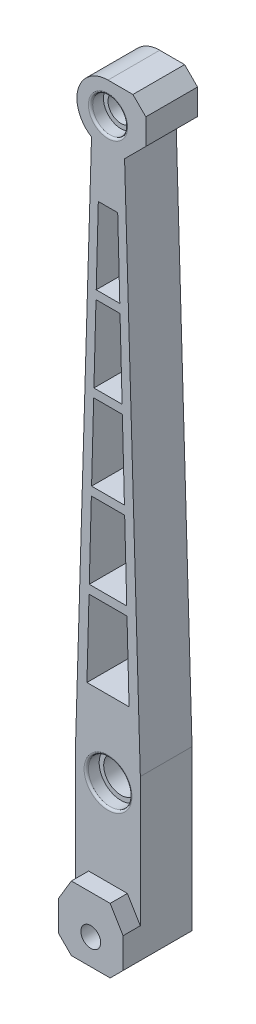
SolidWorks part; units mm, degrees
ref_plane "前视基准面" through (0, 0, 0) normal (0, 0, 1) x (1, 0, 0)
ref_plane "上视基准面" through (0, 0, 0) normal (0, 1, 0) x (1, 0, 0)
ref_plane "右视基准面" through (0, 0, 0) normal (1, 0, 0) x (0, 0, -1)
other "Configuration Table"
sketch "草图1" plane through (0, 0, 0) normal (0, 0, 1) x (1, 0, 0)
  line L0 (0, 15.6534) -> (0, -12.983) construction
  line L1 (-3.6154, 90) -> (-7.5, -40)
  line L2 (-7.5, -80) -> (7.5, -80)
  line L3 (-7.5, -80) -> (-7.5, -40)
  line L4 (-3.6154, 90) -> (3.6154, 90)
  line L5 (7.5, -80) -> (7.5, -40)
  line L6 (-7.5, -80) -> (4.7809, 50.996) construction
  line L7 (-4.7809, 50.996) -> (7.5, -80) construction
  line L8 (3.6154, 90) -> (7.5, -40)
  circle A0 centre (0, -74) radius 2.3
  point P1 (0, 0)
  dimension "D3" = 4.6
  dimension "D1" = 15
  dimension "D2" = 40
  dimension "D4" = 6
  dimension "D5" = 130
extrude "凸台-拉伸1" add sketch "草图1" along normal blind 12
sketch "草图2" plane through (0, 0, 12) normal (0, 0, 1) x (1, 0, 0)
  line L0 (-7.5, -80) -> (7.5, -80) construction
  circle A0 centre (0, -45) radius 5.05
  dimension "D1" = 10.1
  dimension "D2" = 35
extrude "切除-拉伸1" cut sketch "草图2" against normal blind 3
sketch "草图3" plane through (0, 0, 0) normal (0, 0, -1) x (-1, 0, 0)
  circle A0 centre (0, -45) radius 5.05 construction
  circle A1 centre (0, -45) radius 5.05
extrude "切除-拉伸2" cut sketch "草图3" against normal blind 3
sketch "草图4" plane through (0, 0, 9) normal (0, 0, 1) x (1, 0, 0)
  circle A0 centre (0, -45) radius 4
  dimension "D1" = 8
extrude "切除-拉伸3" cut sketch "草图4" against normal blind 15
sketch "草图6" plane through (0, 0, 12) normal (0, 0, 1) x (1, 0, 0)
  line L4 (4.8881, -27.2982) -> (4.4035, -9.2982)
  line L18 (-3.865, 10.7018) -> (3.865, 10.7018)
  line L19 (-2.7342, 52.7018) -> (2.7342, 52.7018)
  line L20 (-3.2727, 32.7018) -> (3.2727, 32.7018)
  line L21 (4.3496, -7.2982) -> (3.865, 10.7018)
  line L22 (-4.3496, -7.2982) -> (4.3496, -7.2982)
  line L23 (-4.8881, -27.2982) -> (4.8881, -27.2982)
  line L24 (-3.8112, 12.7018) -> (3.8112, 12.7018)
  line L25 (-2.7881, 50.7018) -> (2.7881, 50.7018)
  line L26 (-3.3265, 30.7018) -> (3.3265, 30.7018)
  line L27 (-4.4035, -9.2982) -> (-4.8881, -27.2982)
  line L28 (-4.4035, -9.2982) -> (4.4035, -9.2982)
  line L31 (-2.2496, 70.7018) -> (2.2496, 70.7018)
  line L32 (3.8112, 12.7018) -> (3.3265, 30.7018)
  line L33 (-3.865, 10.7018) -> (-4.3496, -7.2982)
  line L34 (3.2727, 32.7018) -> (2.7881, 50.7018)
  line L35 (-3.3265, 30.7018) -> (-3.8112, 12.7018)
  line L36 (2.7342, 52.7018) -> (2.2496, 70.7018)
  line L37 (-2.7881, 50.7018) -> (-3.2727, 32.7018)
  line L39 (-2.2496, 70.7018) -> (-2.7342, 52.7018)
extrude "切除-拉伸4" cut sketch "草图6" against normal blind 15
chamfer "倒角1" distance 3 angle 45 2 edges at (-7.5, -80, 6) (7.5, -80, 6)
sketch "草图7" plane through (0, 0, 12) normal (0, 0, 1) x (1, 0, 0)
  line L0 (-3.8444, 82.3364) -> (3.8444, 82.3364)
  line L1 (-3.6154, 90) -> (-7.5, -40) construction
  line L2 (7.5, -40) -> (3.6154, 90) construction
  line L3 (0, 90) -> (0, 86.1761) construction
  line L5 (3.8444, 82.3364) -> (8.7795, 87.2715)
  line L6 (8.7795, 87.2715) -> (8.7795, 96.2231)
  line L7 (8.7795, 96.2231) -> (-8.7795, 96.2231)
  line L8 (-8.7795, 87.2715) -> (-8.7795, 96.2231)
  line L9 (-3.8444, 82.3364) -> (-8.7795, 87.2715)
  point P13 (0, 96.2231)
extrude "凸台-拉伸2" add sketch "草图7" against normal blind 12
sketch "草图8" plane through (0, 0, 12) normal (0, 0, 1) x (1, 0, 0)
  line L0 (-4.5, -80) -> (4.5, -80) construction
  circle A0 centre (0, 89) radius 3
  dimension "D2" = 6
  dimension "D1" = 169
extrude "切除-拉伸5" cut sketch "草图8" against normal blind 12
chamfer "倒角2" distance 3 angle 45 2 edges at (-8.7795, 96.2231, 6) (8.7795, 96.2231, 6)
sketch "草图9" plane through (0, 0, 12) normal (0, 0, 1) x (1, 0, 0)
  line L0 (-7.5, -70) -> (-4.5, -65)
  line L1 (-4.5, -65) -> (4.5, -65)
  line L2 (4.5, -65) -> (7.5, -70)
  line L14 (5.7795, 96.2231) -> (-5.7795, 96.2231)
  line L15 (-5.7795, 96.2231) -> (-8.7795, 93.2231)
  line L16 (-8.7795, 93.2231) -> (-8.7795, 87.2715)
  line L17 (-8.7795, 87.2715) -> (-3.8444, 82.3364)
  line L18 (-3.8444, 82.3364) -> (-7.5, -40)
  line L19 (-7.5, -40) -> (-7.5, -77)
  line L20 (-7.5, -77) -> (-4.5, -80)
  line L21 (-4.5, -80) -> (4.5, -80)
  line L22 (4.5, -80) -> (7.5, -77)
  line L23 (7.5, -77) -> (7.5, -40)
  line L24 (7.5, -40) -> (3.8444, 82.3364)
  line L33 (-7.5, -70) -> (-7.5, -77)
  line L34 (-7.5, -77) -> (-4.5, -80)
  line L35 (-4.5, -80) -> (4.5, -80)
  line L36 (4.5, -80) -> (7.5, -77)
  line L37 (7.5, -77) -> (7.5, -70)
  line L43 (3.8444, 82.3364) -> (8.7795, 87.2715)
  line L44 (8.7795, 87.2715) -> (8.7795, 93.2231)
  line L45 (8.7795, 93.2231) -> (5.7795, 96.2231)
  circle A0 centre (0, -74) radius 2.3
  dimension "D2" = 15
  dimension "D3" = 10
  dimension "D4" = 10
  dimension "D1" = 0
extrude "凸台-拉伸4" add sketch "草图9" along normal blind 4
fillet "圆角1" radius 0.5 2 edges at (-5.05, -45, 0) (5.05, -45, 12)
sketch "草图10" plane through (0, 0, 12) normal (0, 0, 1) x (1, 0, 0)
  line L1 (-5.7795, 96.2231) -> (0, 96.2231)
  line L7 (-3.8444, 82.3364) -> (-3.8444, 82.885)
  line L8 (-8.7795, 87.2715) -> (-3.8444, 82.3364)
  line L9 (-8.7795, 93.2231) -> (-8.7795, 87.2715)
  line L10 (-5.7795, 96.2231) -> (-8.7795, 93.2231)
  arc A0 (0, 96.2231) -> (-3.8444, 82.885) centre (0, 89) ccw
  point P21 (-2.8897, 96.2231)
extrude "切除-拉伸6" cut sketch "草图10" against normal blind 22
sketch "草图11" plane through (0, 0, 12) normal (0, 0, 1) x (1, 0, 0)
  circle A0 centre (0, 89) radius 4.05
  dimension "D1" = 8.1
extrude "切除-拉伸7" cut sketch "草图11" against normal blind 3
ref_plane "基准面1" through (0, 0, 6) normal (0, 0, 1) x (1, 0, 0)
mirror "镜向1" about plane through (0, 0, 6) normal (0, 0, 1) of "切除-拉伸7"
fillet "圆角2" radius 0.5 2 edges at (4.05, 89, 0) (4.05, 89, 12)
